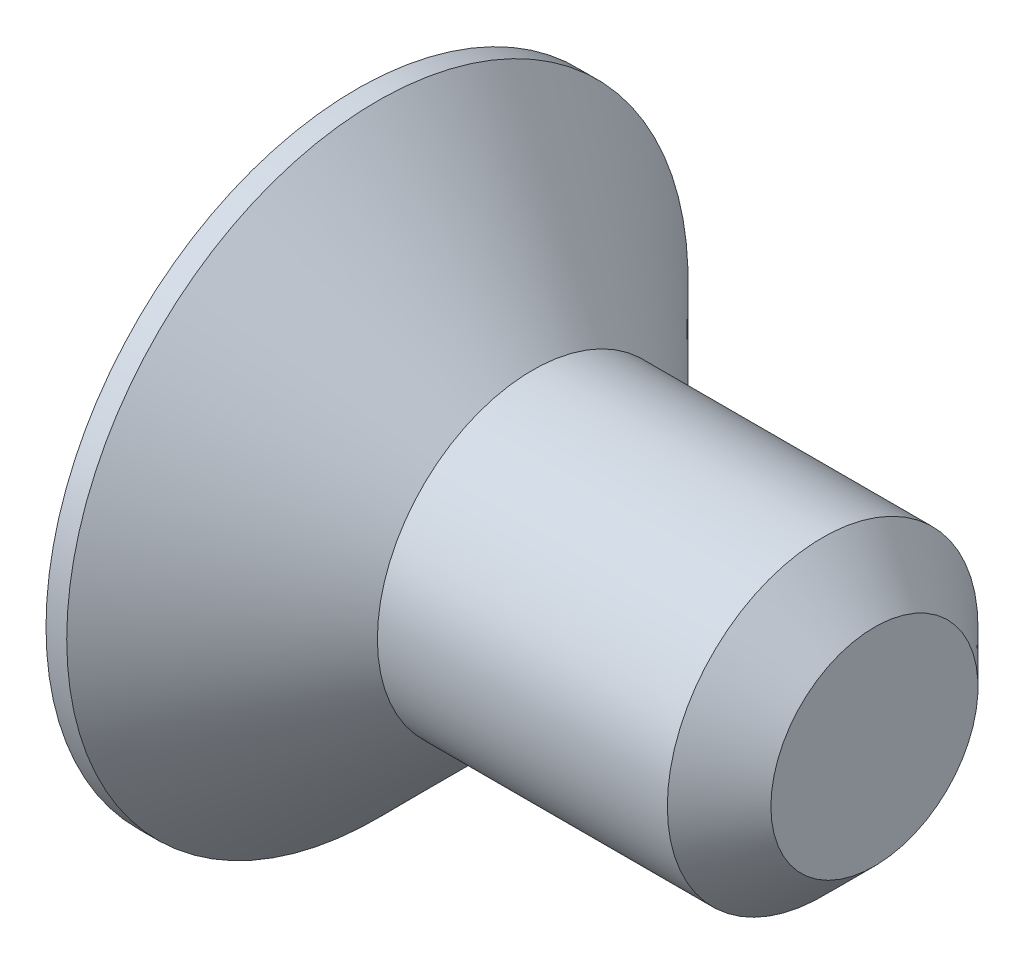
SolidWorks part; units mm, degrees
material "SUS304相当"
ref_plane "Front Plane" through (0, 0, 0) normal (0, 0, 1) x (1, 0, 0)
ref_plane "Top Plane" through (0, 0, 0) normal (0, 1, 0) x (1, 0, 0)
ref_plane "Right Plane" through (0, 0, 0) normal (1, 0, 0) x (0, 0, -1)
sketch "Sketch1" plane through (0, 0, 0) normal (0, 0, 1) x (1, 0, 0)
  line L0 (-1.7, 0) -> (3.3, 0) construction
  line L2 (0, -1.5) -> (2.8, -1.5)
  line L4 (-1.7, -3) -> (-1.5, -3)
  line L5 (3.3, -1) -> (3.3, 0)
  line L6 (-1.7, -3) -> (-1.7, 0)
  line L7 (-1.7, 0) -> (3.3, 0)
  line L9 (-1.5, -3) -> (0, -1.5)
  line L11 (2.8, -1.5) -> (3.3, -1)
  line L12 (3.3, 1) -> (2.8, 1.5) construction
  point P8 (-1.7, -3.36)
  point P12 (-1.7, 3.36)
  point P13 (2.8, -1.5)
  point P14 (-1.7, 3)
  dimension "L" = 5
  dimension "D1" = 45
  dimension "M" = 3
  dimension "Pitch" = 0.5
  dimension "BLT_3" = 0.5
  dimension "D2" = 45
  dimension "BLT_1" = 6.72
  dimension "E" = 1.7
  dimension "A" = 6
revolve "Revolve1" add sketch "Sketch1" angle 360 about L0
cosmetic thread "Thread1"
sketch "Sketch2" plane through (-1.7, 0, 0) normal (-1, 0, 0) x (0, 0, 1)
  line L1 (0, 1.1547) -> (-1, 0.5774)
  line L2 (-1, 0.5774) -> (-1, -0.5774)
  line L3 (-1, -0.5774) -> (0, -1.1547)
  line L4 (0, -1.1547) -> (1, -0.5774)
  line L5 (1, -0.5774) -> (1, 0.5774)
  line L6 (1, 0.5774) -> (0, 1.1547)
  circle A0 centre (0, 0) radius 1 construction
  dimension "B" = 2
extrude "Cut-Extrude1" cut sketch "Sketch2" against normal blind 1.1
equation "\"Pitch\"= iif ( \"M\" = 10 , 1.5 , iif ( \"M\" = 8 , 1.25 , iif ( \"M\" = 6 , 1 , iif ( \"M\" = 5 , 0.8 , iif ( \"M\" = 4 , 0.7 , iif ( \"M\" = 3 , 0.5 , iif ( \"M\" = 2.5 , 0.45 , 0.4 ) ) ) ) ) ) )"
equation "\"Factor\"= 1.082532"
equation "\"ATD_1\"= round ( \"M\" - \"Factor\" * \"Pitch\" , 3 )"
equation "\"BLT_3@Sketch1\"= \"Pitch\""
